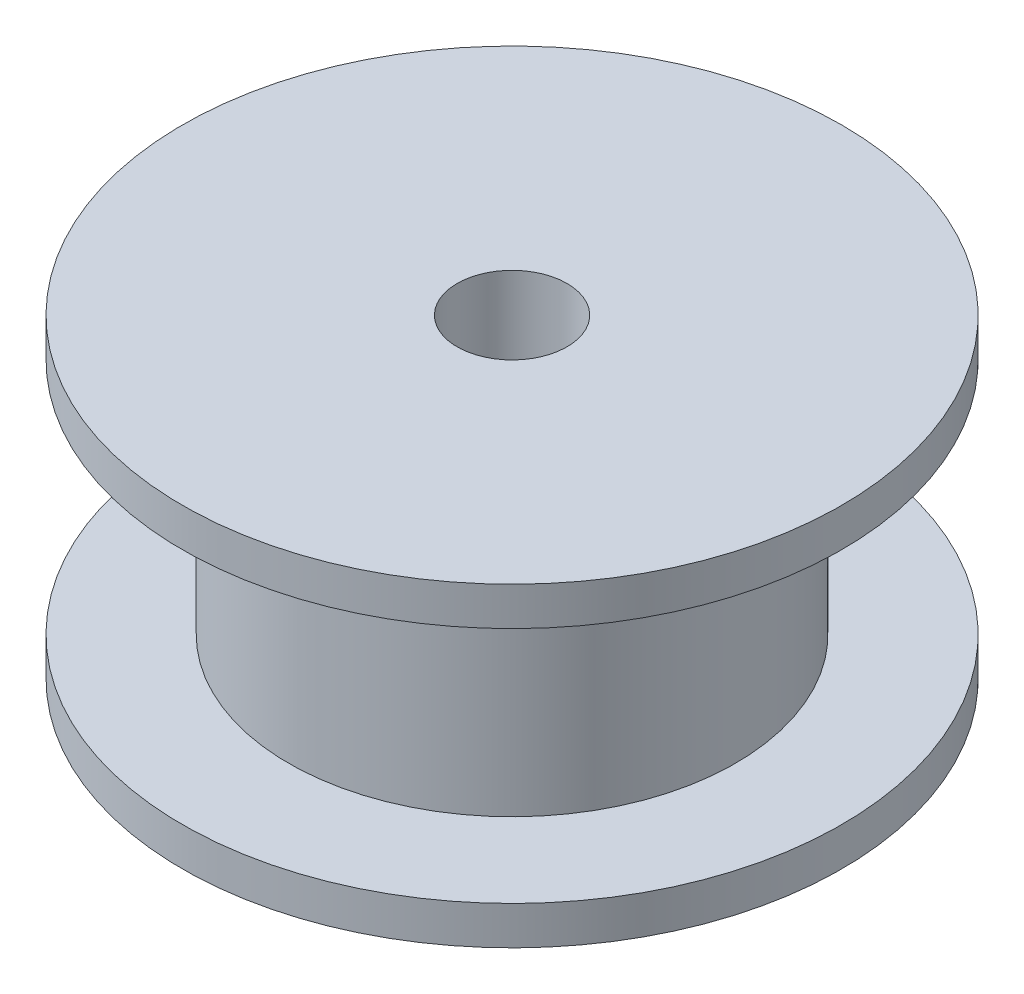
SolidWorks part; units mm, degrees
ref_plane "Plano frontal" through (0, 0, 0) normal (0, 0, 1) x (1, 0, 0)
ref_plane "Plano superior" through (0, 0, 0) normal (0, 1, 0) x (1, 0, 0)
ref_plane "Plano direito" through (0, 0, 0) normal (1, 0, 0) x (0, 0, -1)
sketch "Esboço1" plane through (0, 0, 0) normal (0, 0, 1) x (1, 0, 0)
  line L0 (1.5, 8.6) -> (9, 8.6)
  line L1 (9, 8.6) -> (9, 7.55)
  line L2 (9, 7.55) -> (6.1, 7.55)
  line L3 (6.1, 7.55) -> (6.1, 1.05)
  line L4 (6.1, 1.05) -> (9, 1.05)
  line L5 (9, 1.05) -> (9, 0)
  line L6 (9, 0) -> (1.5, 0)
  line L7 (1.5, 8.6) -> (1.5, 0)
  line L8 (0, 0) -> (0, 12.4153) construction
  dimension "D1" = 8.6
  dimension "D2" = 18
  dimension "D3" = 3
  dimension "D4" = 12.2
  dimension "D5" = 6.5
revolve "Revolução1" add sketch "Esboço1" angle 360 about L8
